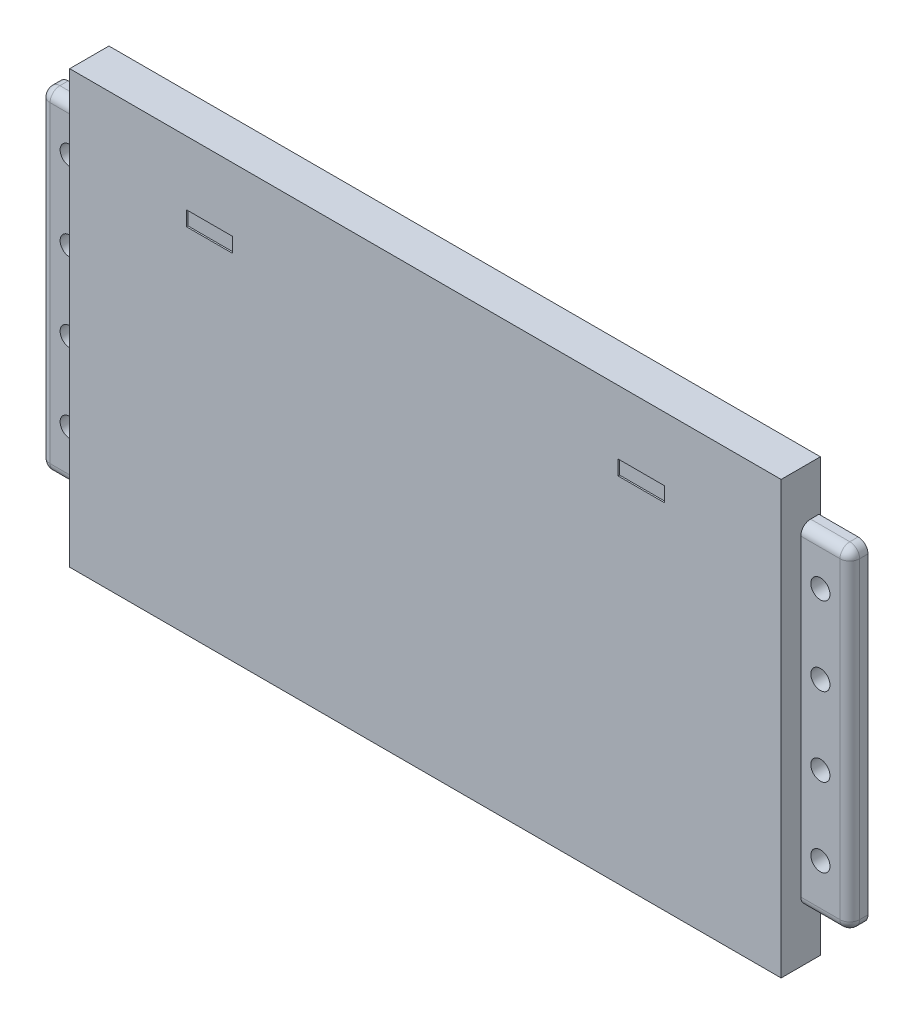
SolidWorks part; units mm, degrees
ref_plane "Front Plane" through (0, 0, 0) normal (0, 0, 1) x (1, 0, 0)
ref_plane "Top Plane" through (0, 0, 0) normal (0, 1, 0) x (1, 0, 0)
ref_plane "Right Plane" through (0, 0, 0) normal (1, 0, 0) x (0, 0, -1)
sketch "Sketch1" plane through (0, 0, 0) normal (0, 0, 1) x (1, 0, 0)
  line L1 (-725, 440) -> (725, 440)
  line L2 (-725, 440) -> (-725, -440)
  line L3 (-725, -440) -> (725, -440)
  line L4 (725, 440) -> (725, -440)
  dimension "D1" = 725
  dimension "D2" = 1450
  dimension "D3" = 880
  dimension "D4" = 440
extrude "Boss-Extrude1" add sketch "Sketch1" along normal mid plane 80
shell "Shell1" thickness 3
sketch "Sketch2" plane through (0, 0, 0) normal (0, 0, 1) x (1, 0, 0)
  line L0 (0, 0) -> (0, -162.6097) construction
  line L1 (725, 440) -> (-725, 440) construction
  line L2 (-487, 310) -> (-393, 310)
  line L3 (-487, 310) -> (-487, 280)
  line L4 (-487, 280) -> (-393, 280)
  line L5 (-393, 310) -> (-393, 280)
  line L6 (-725, 440) -> (-725, -440) construction
  line L7 (487, 310) -> (487, 280)
  line L8 (487, 280) -> (393, 280)
  line L9 (393, 310) -> (393, 280)
  line L10 (487, 310) -> (393, 310)
  dimension "D1" = 94
  dimension "D2" = 30
  dimension "D3" = 130
  dimension "D4" = 238
extrude "Cut-Extrude1" cut sketch "Sketch2" along normal blind 118
sketch "Sketch3" plane through (725, 0, 0) normal (1, 0, 0) x (0, 0, -1)
  line L0 (37, -437) -> (37, 437) construction
  line L1 (37, 340) -> (0, 340)
  line L2 (37, 340) -> (37, -337)
  line L3 (37, -337) -> (0, -337)
  line L4 (0, 340) -> (0, -337)
  line L5 (-40, 440) -> (40, 440) construction
  line L6 (-37, -437) -> (37, -437) construction
  point P6 (18.5, 340)
  dimension "D1" = 100
  dimension "D2" = 100
extrude "Boss-Extrude2" add sketch "Sketch3" along normal blind 100
fillet "Fillet1" radius 20 5 edges at (775, 340, 0) (775, -337, 0) (825, 1.5, 0) (825, -337, -18.5) (825, 340, -18.5)
sketch "Sketch4" plane through (0, 0, 0) normal (0, 0, 1) x (1, 0, 0)
  circle A0 centre (765, 246.9277) radius 19.4943
  circle A1 centre (765, 86.9277) radius 19.4943
  circle A2 centre (765, -73.0723) radius 19.4943
  circle A3 centre (765, -233.0723) radius 19.4943
  dimension "D1" = 4
extrude "Cut-Extrude2" cut sketch "Sketch4" against normal blind 100
mirror "Mirror1" about plane through (0, 0, 0) normal (1, 0, 0) of "Fillet1", "Cut-Extrude2", "Boss-Extrude2"
